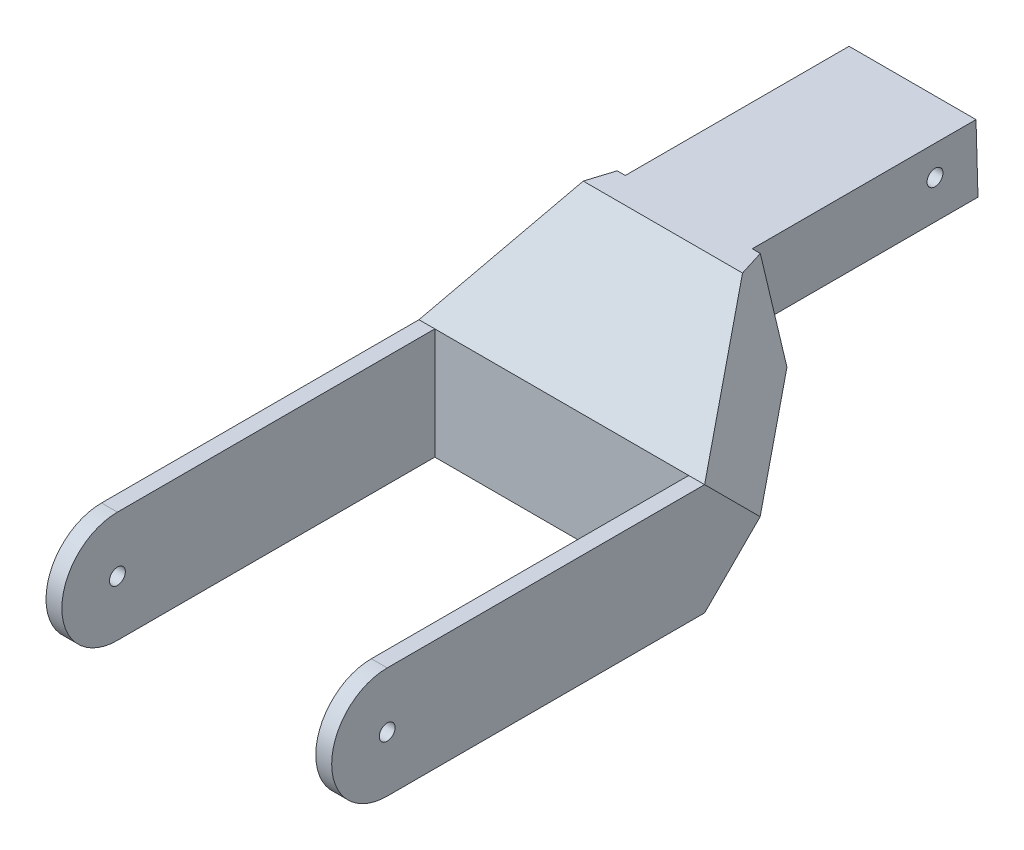
SolidWorks part; units mm, degrees
ref_plane "前视基准面" through (0, 0, 0) normal (0, 0, 1) x (1, 0, 0)
ref_plane "上视基准面" through (0, 0, 0) normal (0, 1, 0) x (1, 0, 0)
ref_plane "右视基准面" through (0, 0, 0) normal (1, 0, 0) x (0, 0, -1)
other "Configuration Table"
sketch "草图1" plane through (0, 0, 0) normal (1, 0, 0) x (0, 0, -1)
  line L1 (6.0355, 5.5899) -> (-13.9645, 5.5899)
  line L2 (6.0355, 5.5899) -> (6.0355, -4.4101)
  line L3 (6.0355, -4.4101) -> (-13.9645, -4.4101)
  line L4 (-13.9645, 5.5899) -> (-13.9645, -4.4101)
  line L5 (6.0355, 5.5899) -> (-13.9645, -4.4101) construction
  line L6 (6.0355, -4.4101) -> (-13.9645, 5.5899) construction
  point P0 (-3.9645, 0.5899)
  dimension "D1" = 20
  dimension "D2" = 10
extrude "凸台-拉伸1" add sketch "草图1" along normal blind 9
sketch "草图2" plane through (9, 0, 0) normal (1, 0, 0) x (0, 0, -1)
  line L2 (-13.9645, -4.4101) -> (-13.9645, -0.9101)
  line L5 (-13.9645, -0.9101) -> (-3.9645, -0.9101)
  line L6 (-13.9645, -4.4101) -> (-3.9645, -4.4101)
  line L8 (-3.9645, -0.9101) -> (0.0355, 3.0899)
  line L9 (0.0355, 3.0899) -> (6.0355, 3.0899)
  line L10 (-13.9645, -4.4101) -> (6.0355, -4.4101) construction
  line L12 (-3.9645, -4.4101) -> (0.0355, -0.4101)
  line L13 (0.0355, -0.4101) -> (6.0355, -0.4101)
  line L14 (6.0355, -4.4101) -> (6.0355, 5.5899) construction
  line L15 (6.0355, -0.4101) -> (6.0355, 3.0899)
  line M14 (-13.9645, -4.4101) -> (6.0355, -4.4101)
  line M15 (6.0355, -4.4101) -> (6.0355, 5.5899)
  dimension "D1" = 3.5
  dimension "D2" = 10
  dimension "D3" = 10
  dimension "D4" = 4
  dimension "D5" = 3.5
extrude "切除-拉伸3" cut sketch "草图2" against normal blind 9 contours L13 L12 M14 M15
sketch "草图6" plane through (9, 0, 0) normal (1, 0, 0) x (0, 0, -1)
  line L0 (-13.9645, -0.9101) -> (-3.9645, -0.9101)
  line L1 (-13.9645, 5.5899) -> (-13.9645, -4.4101) construction
  line L2 (-3.9645, -0.9101) -> (0.0355, 3.0899)
  line L3 (0.0355, 3.0899) -> (6.0355, 3.0899)
  line L4 (6.0355, -0.4101) -> (6.0355, 5.5899) construction
  line L5 (-3.9645, -4.4101) -> (0.0355, -0.4101) construction
  line L6 (0.0355, -0.4101) -> (6.0355, -0.4101) construction
  dimension "D1" = 10
  dimension "D2" = 3.5
extrude "切除-拉伸4" cut sketch "草图6" against normal blind 9 and the other way through all contours L0 L2 L3
sketch "草图8" plane through (9, 0, 0) normal (1, 0, 0) x (0, 0, -1)
  line L0 (-13.9645, -4.4101) -> (-13.9645, -0.9101)
  arc A0 (-13.9645, -0.9101) -> (-13.9645, -4.4101) centre (-13.9645, -2.6601) ccw
extrude "凸台-拉伸2" add sketch "草图8" against normal blind 9
sketch "草图9" plane through (9, 0, 0) normal (1, 0, 0) x (0, 0, -1)
  line L0 (6.0355, -0.4101) -> (6.0355, 3.0899)
  arc A0 (6.0355, 3.0899) -> (6.0355, -0.4101) centre (6.0355, 1.3399) cw
extrude "凸台-拉伸3" add sketch "草图9" against normal blind 9
sketch "草图10" plane through (0, -0.9101, 0) normal (0, 1, 0) x (1, 0, 0)
  line L0 (9, -3.9645) -> (0, -3.9645) construction
  line L1 (8.5, -16.9645) -> (0.5, -16.9645)
  line L2 (8.5, -16.9645) -> (8.5, -3.9645)
  line L3 (8.5, -3.9645) -> (0.5, -3.9645)
  line L4 (0.5, -16.9645) -> (0.5, -3.9645)
  line L5 (8.5, -16.9645) -> (0.5, -3.9645) construction
  line L6 (8.5, -3.9645) -> (0.5, -16.9645) construction
  line L7 (0, -3.9645) -> (0, -13.9645) construction
  point P0 (4.5, -10.4645)
  dimension "D1" = 8
  dimension "D2" = 0.5
  dimension "D3" = 13
extrude "切除-拉伸5" cut sketch "草图10" against normal blind 9
sketch "草图12" plane through (0, 3.0899, 0) normal (0, 1, 0) x (1, 0, 0)
  line L14 (9, 6.0355) -> (9, 0.0355) construction
  line L15 (6.5, 0.0355) -> (9, 0.0355)
  line L17 (6.5, 0.0355) -> (6.5, 12.0355)
  line L18 (6.5, 12.0355) -> (9, 12.0355)
  line L19 (9, 0.0355) -> (9, 12.0355)
  line L20 (6.5, 0.0355) -> (9, 12.0355) construction
  line L21 (6.5, 12.0355) -> (9, 0.0355) construction
  line L22 (9, 0.0355) -> (0, 0.0355) construction
  point P0 (4.5, 4.6422)
  point P1 (4.5, 4.6422)
  point P2 (7.75, 6.0355)
  dimension "D1" = 2.5
  dimension "D2" = 12
  dimension "D3" = 0
extrude "切除-拉伸6" cut sketch "草图12" against normal blind 9
sketch "草图13" plane through (0, 3.0899, 0) normal (0, 1, 0) x (1, 0, 0)
  line L0 (6.5, 0.0355) -> (0, 0.0355) construction
  line L1 (2.5, 0.0355) -> (0, 0.0355)
  line L2 (2.5, 0.0355) -> (2.5, 7.7855)
  line L3 (2.5, 7.7855) -> (0, 7.7855)
  line L4 (0, 0.0355) -> (0, 7.7855)
  line L5 (2.5, 0.0355) -> (0, 7.7855) construction
  line L6 (2.5, 7.7855) -> (0, 0.0355) construction
  point P0 (1.25, 3.9105)
  dimension "D1" = 0
  dimension "D2" = 2.5
extrude "切除-拉伸7" cut sketch "草图13" against normal blind 9
sketch "草图14" plane through (0, 1.5272, 1.5272) normal (0, 0.7071, 0.7071) x (1, 0, 0)
  line L0 (2.5, 2.21) -> (0, -3.4469)
  line L1 (2.5, 2.21) -> (-4.3729, 5.0398)
  line L2 (0, -3.4469) -> (-6.8729, -0.6171)
  line L3 (-4.3729, 5.0398) -> (-6.8729, -0.6171)
extrude "切除-拉伸8" cut sketch "草图14" against normal blind 9
sketch "草图15" plane through (0, 1.5272, 1.5272) normal (0, 0.7071, 0.7071) x (1, 0, 0)
  line L0 (6.5, 2.21) -> (9, -3.4469)
  line L1 (6.5, 2.21) -> (10.1734, 5.6569)
  line L2 (9, -3.4469) -> (12.6734, 0)
  line L3 (10.1734, 5.6569) -> (12.6734, 0)
extrude "切除-拉伸9" cut sketch "草图15" against normal blind 9
sketch "草图25" plane through (0, 0, 3.9645) normal (0, 0, 1) x (1, 0, 0)
  point P0 (4.3043, -2.7547)
sketch "草图26" plane through (0, 0, 0) normal (-1, 0, 0) x (0, 0, 1)
  circle A0 centre (13.9645, -2.6601) radius 0.25
  dimension "D1" = 0.5
extrude "切除-拉伸16" cut sketch "草图26" against normal through all
scale "缩放比例1" scale about centroid uniform scaling yes scale factor 2.454545
sketch "草图29" plane through (0, 0, 8.4313) normal (0, 0, 1) x (1, 0, 0)
  line L0 (9.4091, 7.9529) -> (-0.4091, 7.9529) construction
  line L1 (14.1472, 5.9529) -> (-5.222, 5.9529)
  line L2 (14.1472, 5.9529) -> (14.1472, 14.1865)
  line L3 (14.1472, 14.1865) -> (-5.222, 14.1865)
  line L4 (-5.222, 5.9529) -> (-5.222, 14.1865)
  line L5 (14.1472, 5.9529) -> (-5.222, 14.1865) construction
  line L6 (14.1472, 14.1865) -> (-5.222, 5.9529) construction
  point P0 (4.4626, 10.0697)
  dimension "D1" = 2
extrude "切除-拉伸17" cut sketch "草图29" against normal through all
sketch "草图31" plane through (9.4091, 0, 0) normal (1, 0, 0) x (0, 0, -1)
  line L14 (1.3869, 0.6799) -> (19.7449, 0.6799)
  line L15 (1.3869, -0.6381) -> (1.3869, 5.9529) construction
  line L16 (19.7449, 5.9529) -> (1.3869, 5.9529) construction
  line L18 (1.3869, 0.6799) -> (25.5104, 0.6799)
  line L19 (1.3869, 0.6799) -> (1.3869, -1.3142)
  line L20 (1.3869, -1.3142) -> (25.5104, -1.3142)
  line L21 (25.5104, 0.6799) -> (25.5104, -1.3142)
  arc M7 (16.1142, -0.6381) -> (19.7449, 5.9529) centre (16.1142, 3.6574) ccw
  line M9 (1.3869, 5.9529) -> (1.3869, -0.6381)
  line M10 (1.3869, -0.6381) -> (16.1142, -0.6381)
extrude "切除-拉伸18" cut sketch "草图31" against normal blind 10 contours L14 M9 M10 M7
sketch "草图34" plane through (9.4091, 0, 0) normal (1, 0, 0) x (0, 0, -1)
  circle A0 centre (15.5226, 3.6582) radius 0.615
  dimension "D1" = 1.23
extrude "切除-拉伸19" cut sketch "草图34" against normal blind 10
sketch "草图35" plane through (9.4091, 0, 0) normal (1, 0, 0) x (0, 0, -1)
  line L0 (18.6033, 9.0022) -> (19.1691, -10.4249)
  line L1 (18.6033, 9.0022) -> (26.3993, 9.4423)
  line L2 (19.1691, -10.4249) -> (26.9651, -9.9848)
  line L3 (26.3993, 9.4423) -> (26.9651, -9.9848)
extrude "切除-拉伸20" cut sketch "草图35" against normal blind 10
